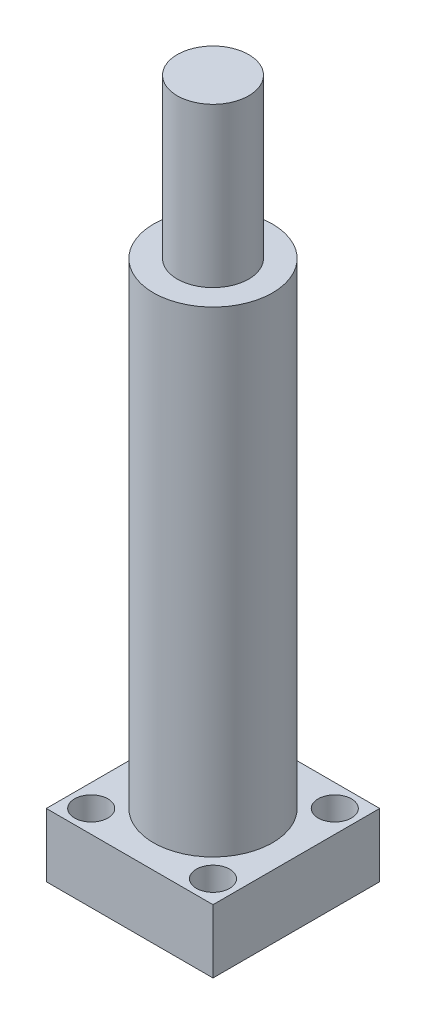
SolidWorks part; units mm, degrees
ref_plane "前视基准面" through (0, 0, 0) normal (0, 0, 1) x (1, 0, 0)
ref_plane "上视基准面" through (0, 0, 0) normal (0, 1, 0) x (1, 0, 0)
ref_plane "右视基准面" through (0, 0, 0) normal (1, 0, 0) x (0, 0, -1)
other "Configuration Table"
sketch "草图1" plane through (0, 0, 0) normal (0, 1, 0) x (1, 0, 0)
  circle A0 centre (0, 0) radius 7.5
  dimension "D1" = 15
extrude "凸台-拉伸1" add sketch "草图1" along normal blind 68 contours A0
sketch "草图2" plane through (0, 0, 0) normal (0, -1, 0) x (1, 0, 0)
  line L5 (10.5, -10.5) -> (-10.5, -10.5)
  line L6 (10.5, -10.5) -> (10.5, 10.5)
  line L7 (10.5, 10.5) -> (-10.5, 10.5)
  line L8 (-10.5, -10.5) -> (-10.5, 10.5)
  line L9 (10.5, -10.5) -> (-10.5, 10.5) construction
  line L10 (10.5, 10.5) -> (-10.5, -10.5) construction
  circle A2 centre (-7.6716, 7.6716) radius 2.1
  circle A3 centre (7.6716, -7.6716) radius 2.1
  circle A4 centre (7.6716, 7.6716) radius 2.1
  circle A5 centre (-7.6716, -7.6716) radius 2.1
  point P0 (0, 0)
  dimension "D5" = 4.2
  dimension "D10" = 4
  dimension "D3" = 4.2
  dimension "D7" = 4.2
  dimension "D9" = 4.2
  dimension "D1" = 10.5
  dimension "D2" = 10.5
  dimension "D4" = 4
  dimension "D6" = 4
  dimension "D8" = 4
extrude "凸台-拉伸2" add sketch "草图2" against normal blind 8
sketch "草图3" plane through (0, 68, 0) normal (0, 1, 0) x (1, 0, 0)
  circle A0 centre (0, 0) radius 4.5
  dimension "D1" = 9
extrude "凸台-拉伸3" add sketch "草图3" along normal blind 20
